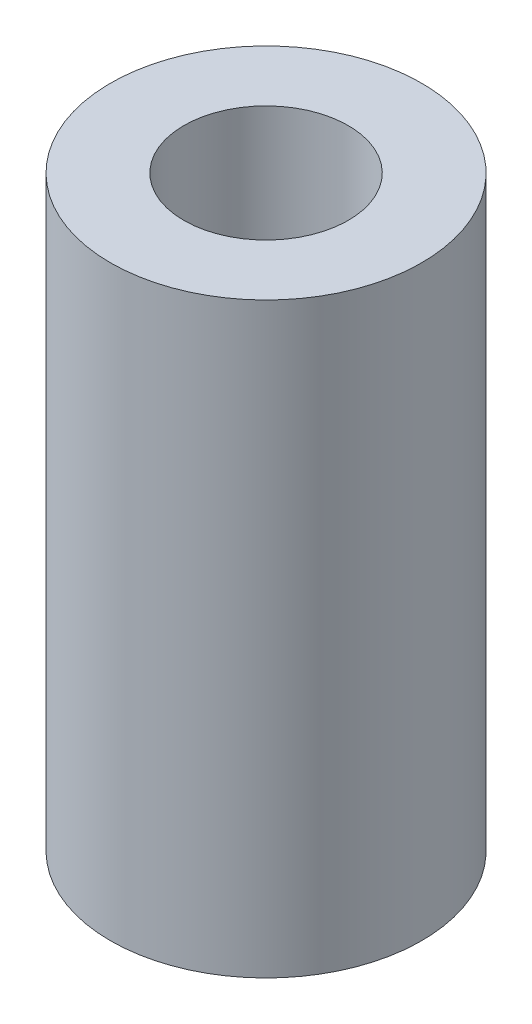
SolidWorks part; units mm, degrees
ref_plane "Front Plane" through (0, 0, 0) normal (0, 0, 1) x (1, 0, 0)
ref_plane "Top Plane" through (0, 0, 0) normal (0, 1, 0) x (1, 0, 0)
ref_plane "Right Plane" through (0, 0, 0) normal (1, 0, 0) x (0, 0, -1)
sketch "Sketch1" plane through (0, 0, 0) normal (0, 1, 0) x (1, 0, 0)
  line L0 (0, 12.1368) -> (0, -11.7091) construction
  circle A0 centre (0, 0) radius 13.25
  circle A1 centre (0, 0) radius 7
  dimension "D1" = 14
  dimension "D2" = 26.5
extrude "Boss-Extrude1" add sketch "Sketch1" along normal mid plane 50
